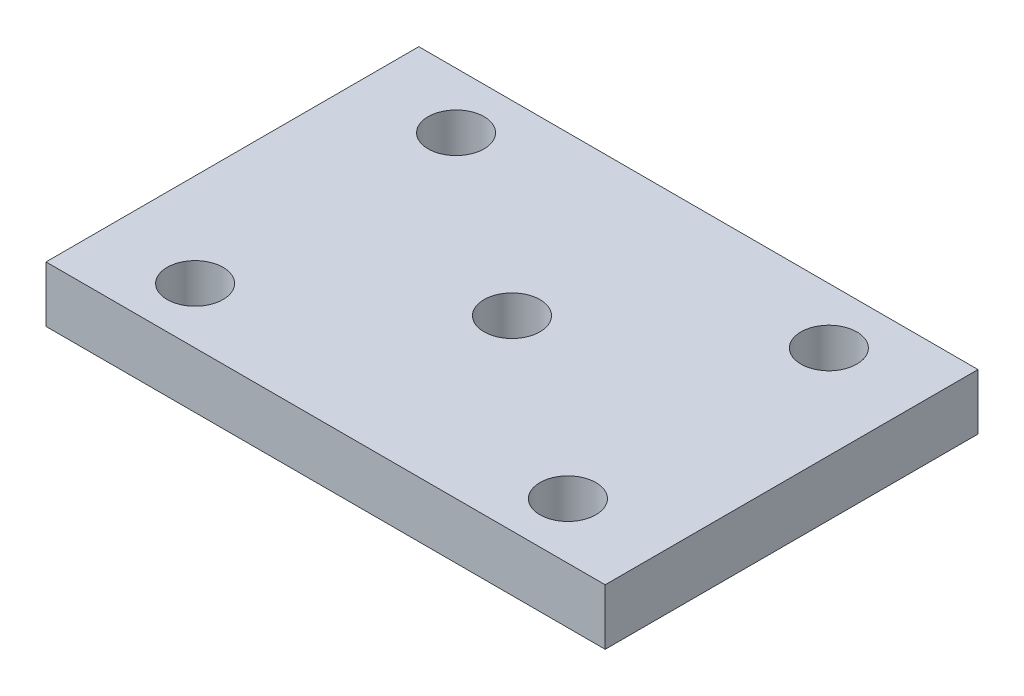
SolidWorks part; units mm, degrees
material "1060 合金"
ref_plane "前视基准面" through (0, 0, 0) normal (0, 0, 1) x (1, 0, 0)
ref_plane "上视基准面" through (0, 0, 0) normal (0, 1, 0) x (1, 0, 0)
ref_plane "右视基准面" through (0, 0, 0) normal (1, 0, 0) x (0, 0, -1)
sketch "草图1" plane through (0, 0, 0) normal (0, 1, 0) x (1, 0, 0)
  line L0 (0, -10) -> (0, 10) construction
  line L1 (-15, 10) -> (15, 10)
  line L2 (-15, 10) -> (-15, -10)
  line L3 (-15, -10) -> (15, -10)
  line L4 (15, 10) -> (15, -10)
  line L5 (-15, 0) -> (15, 0) construction
  circle A0 centre (-10, -7) radius 1.5
  circle A1 centre (10, -7) radius 1.5
  circle A2 centre (10, 7) radius 1.5
  circle A3 centre (-10, 7) radius 1.5
  circle A4 centre (0, 0) radius 1.5
  point P4 (0, -10)
  point P5 (15, 0)
  dimension "D3" = 3
  dimension "D6" = 3
  dimension "D1" = 20
  dimension "D2" = 30
  dimension "D4" = 5
  dimension "D5" = 3
extrude "凸台-拉伸1" add sketch "草图1" along normal blind 3
